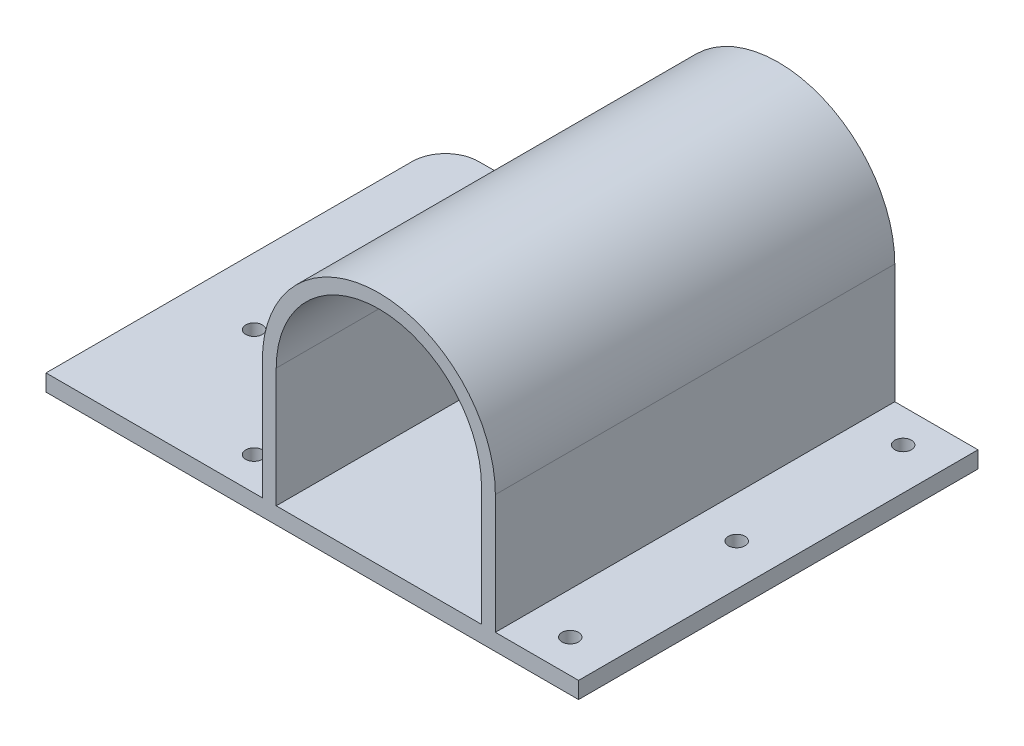
SolidWorks part; units mm, degrees
ref_plane "Front Plane" through (0, 0, 0) normal (0, 0, 1) x (1, 0, 0)
ref_plane "Top Plane" through (0, 0, 0) normal (0, 1, 0) x (1, 0, 0)
ref_plane "Right Plane" through (0, 0, 0) normal (1, 0, 0) x (0, 0, -1)
sketch "Sketch1" plane through (0, 0, 0) normal (0, 0, 1) x (1, 0, 0)
  line L0 (-21, 0) -> (-21, -21.5)
  line L1 (-21, -21.5) -> (-36, -21.5)
  line L2 (-36, -21.5) -> (-36, -24.5)
  line L3 (-36, -24.5) -> (36, -24.5)
  line L4 (36, -24.5) -> (36, -21.5)
  line L5 (36, -21.5) -> (21, -21.5)
  line L6 (21, -21.5) -> (21, 0)
  line L7 (0, 0) -> (-7, 0) construction
  line L8 (0, 0) -> (0, -15.5) construction
  line L9 (-21, -21.5) -> (21, -21.5) construction
  arc A0 (21, 0) -> (-21, 0) centre (0, 0) ccw
  circle A2 centre (0, -15.5) radius 1.65
  circle A3 centre (-13.4234, -7.75) radius 1.65
  circle A4 centre (-13.4234, 7.75) radius 1.65
  circle A5 centre (0, 15.5) radius 1.65
  circle A6 centre (13.4234, 7.75) radius 1.65
  circle A7 centre (13.4234, -7.75) radius 1.65
  circle A8 centre (0, 0) radius 18.5 construction
  circle A9 centre (-7, 0) radius 6.15
  point P15 (0, -18.5)
  point P27 (0, 0)
  dimension "D1" = 42
  dimension "D6" = 3
  dimension "D7" = 3.3
  dimension "D10" = 37
  dimension "D11" = 2.5
  dimension "D12" = 90
  dimension "D3" = 12.3
  dimension "D2" = 7
  dimension "D4" = 72
  dimension "D5" = 3
  dimension "D8" = 15.5
  dimension "D9" = 6
extrude "Boss-Extrude1" add sketch "Sketch1" along normal blind 72
sketch "Sketch2" plane through (0, 0, 72) normal (0, 0, 1) x (1, 0, 0)
  line L0 (-18.5, 0) -> (-18.5, -21.5)
  line L2 (-18.5, -21.5) -> (18.5, -21.5)
  line L3 (18.5, -21.5) -> (18.5, 0)
  line L4 (-21, -21.5) -> (-36, -21.5) construction
  arc A0 (18.5, 0) -> (-18.5, 0) centre (0, 0) ccw
  arc A1 (-18.5, 0) -> (18.5, 0) centre (0, 0) ccw construction
  dimension "D1" = 37
extrude "Cut-Extrude1" cut sketch "Sketch2" against normal blind 57
sketch "Sketch3" plane through (0, -21.5, 0) normal (0, 1, 0) x (1, 0, 0)
  line L0 (0, 0) -> (0, -72) construction
  line L1 (-21, -72) -> (21, -72) construction
  line L2 (-28.5, 0) -> (-28.5, -72) construction
  line L3 (-21, 0) -> (-36, 0) construction
  line L4 (-21, -72) -> (-36, -72) construction
  circle A0 centre (-28.5, -36) radius 1.5
  circle A1 centre (-28.5, -6) radius 1.5
  circle A2 centre (-28.5, -66) radius 1.5
  circle A3 centre (28.5, -66) radius 1.5
  circle A4 centre (28.5, -6) radius 1.5
  circle A5 centre (28.5, -36) radius 1.5
  dimension "D1" = 30
  dimension "D2" = 30
  dimension "D3" = 3
extrude "Cut-Extrude2" cut sketch "Sketch3" against normal through all
sketch "Sketch4" plane through (0, -21.5, 0) normal (0, 1, 0) x (1, 0, 0)
  line L0 (-36, 0) -> (-36, -72)
  line L1 (-36, -72) -> (-60, -72)
  line L2 (-60, -72) -> (-60, 0)
  line L3 (-60, 0) -> (-36, 0)
  line L4 (-48, 0) -> (-48, -72) construction
  circle A0 centre (-48, -46.5) radius 1.5
  circle A1 centre (-48, -10.5) radius 1.5
  dimension "D3" = 36
  dimension "D4" = 3
  dimension "D5" = 10.5
  dimension "D1" = 24
  dimension "D2" = 12
extrude "Boss-Extrude2" add sketch "Sketch4" against normal blind 3
fillet "Fillet1" radius 6 1 edges at (-60, -23, 0)
